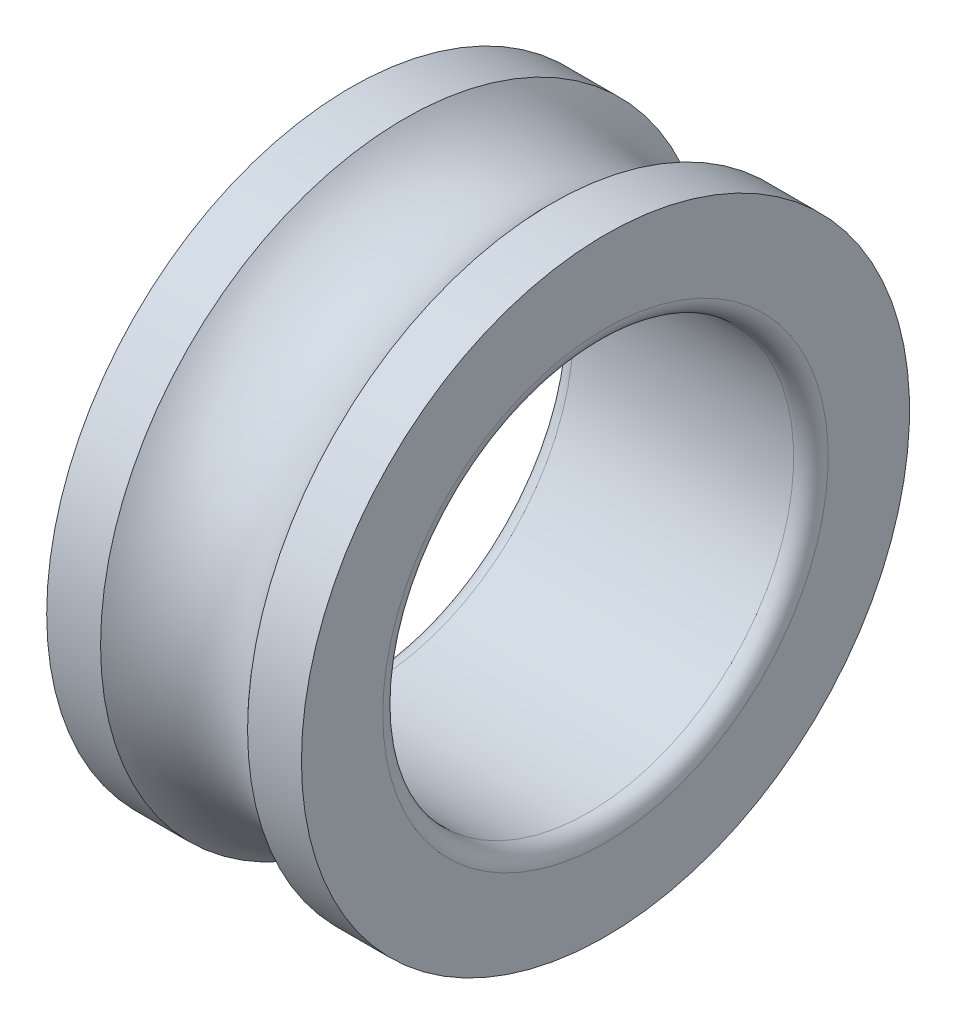
SolidWorks part; units mm, degrees
ref_plane "Ön Düzlem" through (0, 0, 0) normal (0, 0, 1) x (1, 0, 0)
ref_plane "Üst Düzlem" through (0, 0, 0) normal (0, 1, 0) x (1, 0, 0)
ref_plane "Sağ Düzlem" through (0, 0, 0) normal (1, 0, 0) x (0, 0, -1)
sketch "Çizim1" plane through (0, 0, 0) normal (0, 0, 1) x (1, 0, 0)
  line L0 (-12.3367, 0) -> (16.8444, 0) construction
  line L1 (0, 0) -> (0, 25) construction
  line L2 (-15.5, 37) -> (-8.9443, 37)
  line L3 (-15.5, 37) -> (-15.5, 27.1)
  line L4 (-13.4, 25) -> (13.4, 25)
  line L5 (15.5, 37) -> (15.5, 27.1)
  line L6 (-15.5, 37) -> (15.5, 25) construction
  line L7 (-15.5, 25) -> (15.5, 37) construction
  line L8 (8.9443, 37) -> (15.5, 37)
  arc A0 (8.9443, 37) -> (-8.9443, 37) centre (0, 45) cw
  arc A1 (13.4, 25) -> (15.5, 27.1) centre (13.4, 27.1) ccw
  arc A2 (-15.5, 27.1) -> (-13.4, 25) centre (-13.4, 27.1) ccw
  point P3 (0, 31)
  dimension "D5" = 12
  dimension "D6" = 2.1
  dimension "D1" = 31
  dimension "D2" = 25
  dimension "D3" = 37
  dimension "D4" = 8
revolve "Döndür1" add sketch "Çizim1" angle 360 about L0
